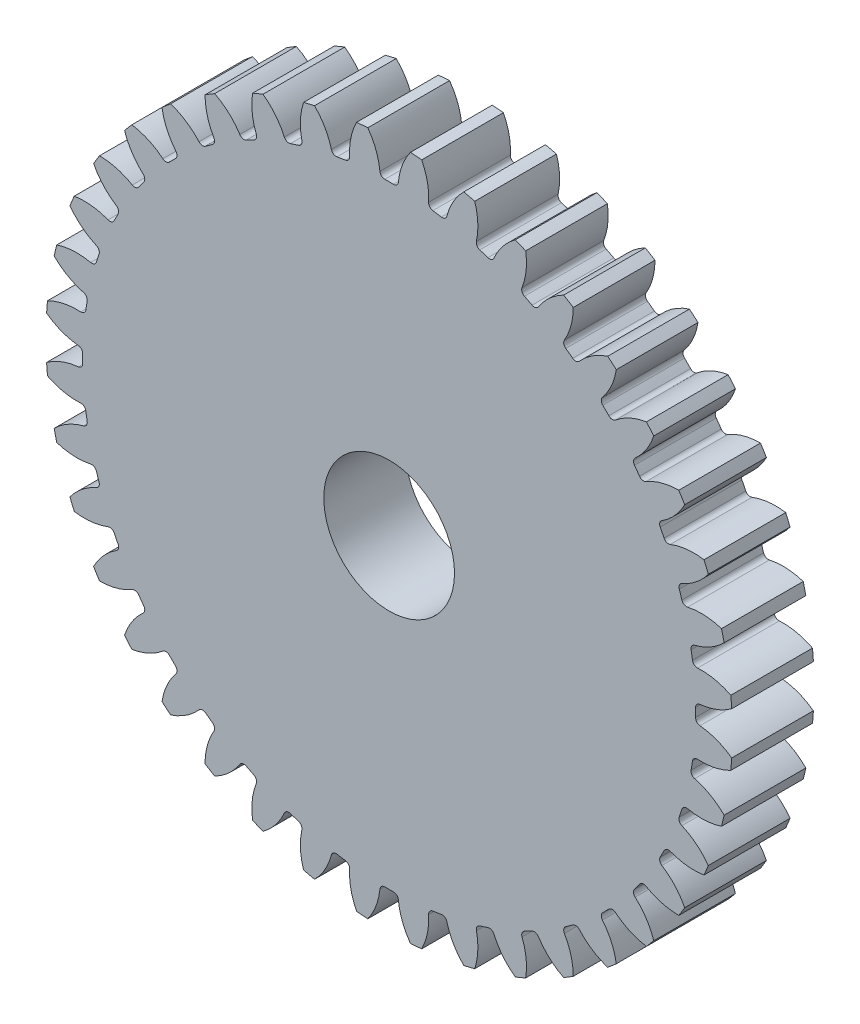
SolidWorks part; units mm, degrees
ref_plane "Płaszczyzna przednia" through (0, 0, 0) normal (0, 0, 1) x (1, 0, 0)
ref_plane "Płaszczyzna górna" through (0, 0, 0) normal (0, 1, 0) x (1, 0, 0)
ref_plane "Płaszczyzna prawa" through (0, 0, 0) normal (1, 0, 0) x (0, 0, -1)
sketch "Sketch1" plane through (0, 0, 0) normal (0, 0, 1) x (1, 0, 0)
  circle A0 centre (0, 0) radius 80
  circle A1 centre (0, 0) radius 84
  circle A2 centre (0, 0) radius 75
  circle A3 centre (0, 0) radius 16
  dimension "D1" = 160
  dimension "D2" = 168
  dimension "D3" = 9
  dimension "D4" = 32
extrude "Boss-Extrude1" add sketch "Sketch1" along normal mid plane 20 contours A1
sketch "Sketch2" plane through (0, 0, 0) normal (0, 0, 1) x (1, 0, 0)
  line L0 (0, 0) -> (0, 84) construction
  line L1 (-3.1408, 79.9383) -> (3.1408, 79.9383) construction
  line L2 (0, 0) -> (-2.1894, 74.968) construction
  line L3 (0, 71.3091) -> (-4.931, 84.8569) construction
  line L4 (0, 0) -> (6.5906, 83.7411) construction
  line L5 (3.1408, 79.9383) -> (9.403, 79.4455) construction
  circle A0 centre (0, 0) radius 84 construction
  arc A1 (-5.9619, 84.7907) -> (-2.1894, 74.968) centre (-18.0708, 74.5042) cw
  arc A2 (5.9619, 84.7907) -> (2.1894, 74.968) centre (18.0708, 74.5042) ccw
  circle A3 centre (0, 0) radius 75 construction
  arc A4 (2.1894, 74.968) -> (-2.1894, 74.968) centre (0, 0) ccw
  circle A8 centre (0, 0) radius 85
  arc A9 (5.9619, 84.7907) -> (-5.9619, 84.7907) centre (0, 0) ccw
  circle A10 centre (0, 0) radius 80 construction
  circle A11 centre (0, 0) radius 84 construction
  circle A12 centre (0, 0) radius 16 construction
  circle A13 centre (0, 0) radius 16
  dimension "D2" = 20
  dimension "D3" = 4.5
  dimension "D1" = 1
extrude "Cut-Extrude1" cut sketch "Sketch2" against normal through all both and the other way through all contours A9 A1 A4 A2 | A13
fillet "Fillet1" radius 1.2 2 edges at (2.1894, 74.968, 0) (-2.1894, 74.968, 0)
pattern_circular "CirPattern1" count 40 over 360 about axis through (0, 0, 0) along (0, 0, 1) of "Cut-Extrude1", "Fillet1"
equation "\"Module\"= 4mm'Modół"
equation "\"Number of Teeth\"= 40'Liczba zębów"
equation "\"D1@Sketch1\"=\"Module\"*\"Number of Teeth\""
equation "\"D2@Sketch1\"=(\"Number of Teeth\"+2) * \"Module\""
equation "\"D3@Sketch1\"=\"Module\" * if( \"Module\"=>1.25,2.25,2.4)"
equation "\"D3@Sketch2\"=180 / \"Number of Teeth\""
equation "\"D1@Fillet1\"=.3 * \"Module\""
equation "\"D1@CirPattern1\"=\"Number of Teeth\""
equation "\"D4@Sketch1\"=(\"Module\"* \"Number of Teeth\") / 5"
